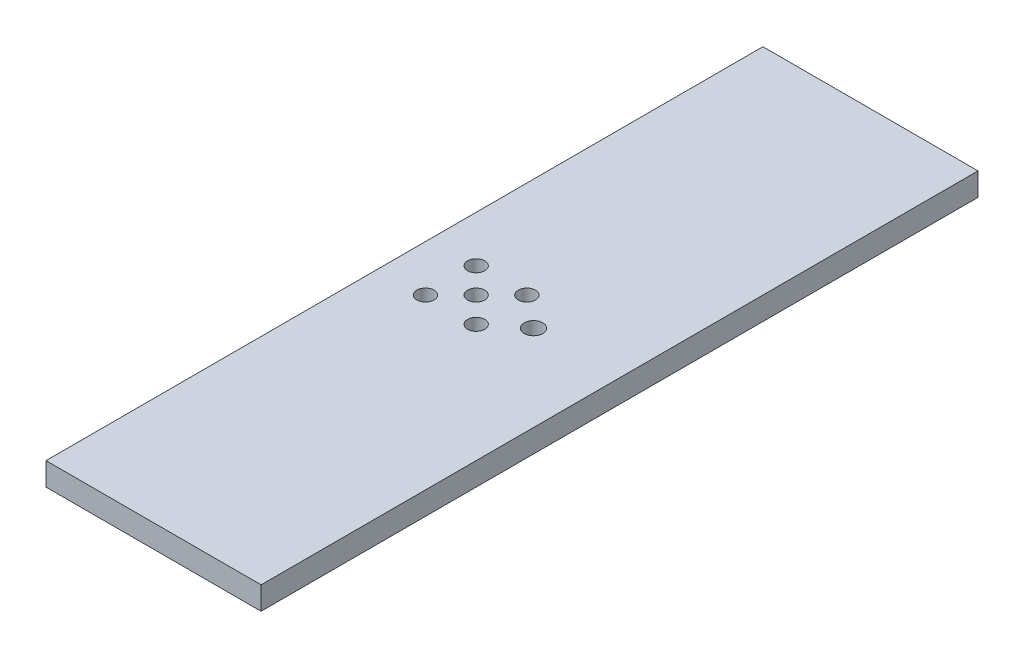
SolidWorks part; units mm, degrees
ref_plane "Front Plane" through (0, 0, 0) normal (0, 0, 1) x (1, 0, 0)
ref_plane "Top Plane" through (0, 0, 0) normal (0, 1, 0) x (1, 0, 0)
ref_plane "Right Plane" through (0, 0, 0) normal (1, 0, 0) x (0, 0, -1)
sketch "Sketch1" plane through (0, 0, 0) normal (0, 1, 0) x (1, 0, 0)
  line L0 (0, 25) -> (15, 25)
  line L1 (15, 25) -> (15, -25)
  line L2 (0, -25) -> (0, 25)
  line L3 (15, -25) -> (0, -25)
  line L7 (0, 0) -> (160.2024, 0) construction
  point P16 (0, 0)
  dimension "D1" = 15
  dimension "D2" = 50
extrude "Boss-Extrude1" add sketch "Sketch1" along normal blind 1.6 contours L2 L0 L1 L3
sketch "Sketch3" plane through (0, 1.6, 0) normal (0, 1, 0) x (1, 0, 0)
  line L0 (3.2322, 1.7678) -> (6.7678, -1.7678) construction
  line L1 (3.2322, -1.7678) -> (6.7678, 1.7678) construction
  line L2 (0, -25) -> (0, 25) construction
  line L3 (0, -25) -> (0, 25) construction
  circle A0 centre (5, 0) radius 0.6
  circle A1 centre (5, 0) radius 2.5 construction
  circle A2 centre (3.2322, 1.7678) radius 0.6
  circle A3 centre (6.7678, 1.7678) radius 0.6
  circle A4 centre (6.7678, -1.7678) radius 0.6
  circle A5 centre (3.2322, -1.7678) radius 0.6
  circle A6 centre (9, 0) radius 0.65
  point P15 (0, 0)
  dimension "D1" = 1.2
  dimension "D2" = 1.3
  dimension "D5" = 5
  dimension "D3" = 4
  dimension "D4" = 5
extrude "M12 mounting holes" cut sketch "Sketch3" against normal up to next
